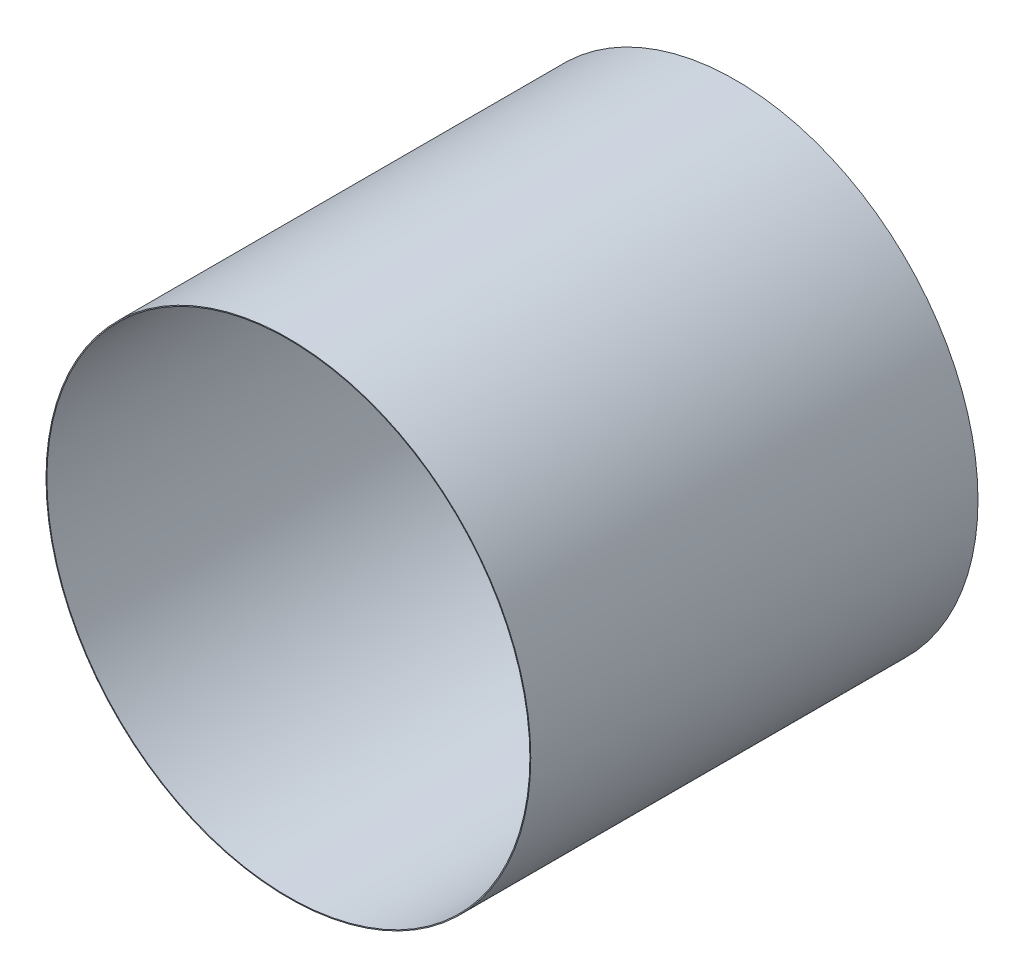
SolidWorks part; units mm, degrees
ref_plane "Front Plane" through (0, 0, 0) normal (0, 0, 1) x (1, 0, 0)
ref_plane "Top Plane" through (0, 0, 0) normal (0, 1, 0) x (1, 0, 0)
ref_plane "Right Plane" through (0, 0, 0) normal (1, 0, 0) x (0, 0, -1)
sketch "Sketch1" plane through (0, 0, 0) normal (0, 0, 1) x (1, 0, 0)
  circle A0 centre (0, 0) radius 13.55
  circle A1 centre (0, 0) radius 13.5
  dimension "D1" = 27
  dimension "D2" = 27.1
extrude "Boss-Extrude1" add sketch "Sketch1" along normal blind 25
